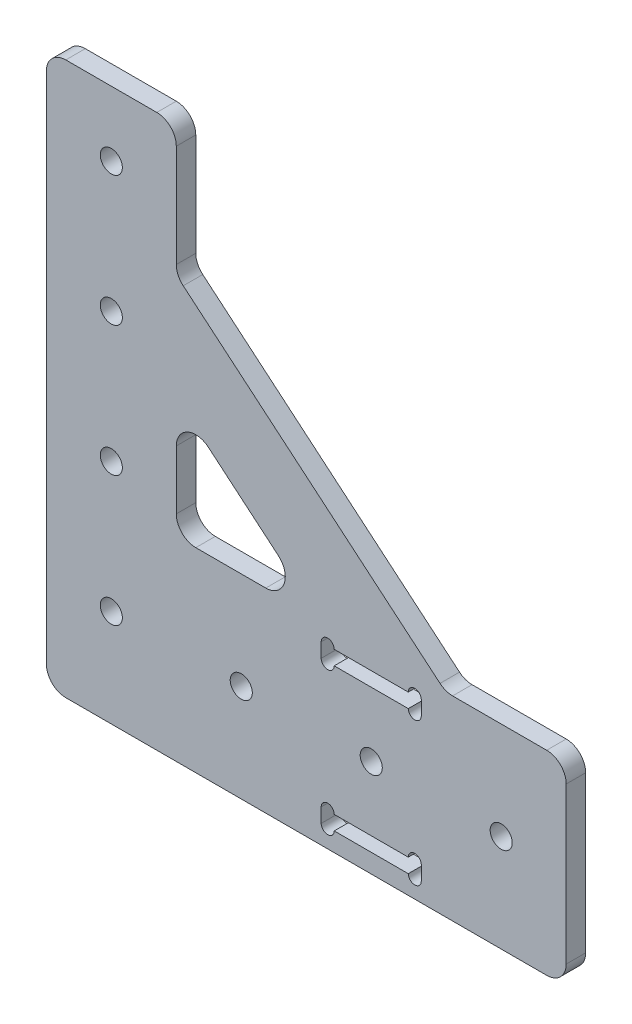
SolidWorks part; units mm, degrees
ref_plane "前视基准面" through (0, 0, 0) normal (0, 0, 1) x (1, 0, 0)
ref_plane "上视基准面" through (0, 0, 0) normal (0, 1, 0) x (1, 0, 0)
ref_plane "右视基准面" through (0, 0, 0) normal (1, 0, 0) x (0, 0, -1)
other "Configuration Table"
sketch "草图1" plane through (0, 0, 0) normal (0, 0, 1) x (1, 0, 0)
  line L0 (0, 85) -> (0, 0)
  line L1 (0, 0) -> (80, 0)
  line L2 (80, 0) -> (80, 30)
  line L3 (80, 30) -> (61.422, 30)
  line L4 (20, 30) -> (20, 48.5)
  line L5 (20, 85) -> (0, 85)
  line L6 (-8.2516, 78.7898) -> (73.8069, 9.7861) construction
  line L7 (20, 48.5) -> (42, 30)
  line L8 (20, 64.8321) -> (20, 85)
  line L9 (20, 64.8321) -> (61.422, 30)
  line L10 (-11.4696, 74.963) -> (70.5889, 5.9593) construction
  line L11 (42, 30) -> (20, 30)
  point P13 (-5.0735, 82.4031)
  point P14 (77.2855, 13.7621)
  dimension "D1" = 20
  dimension "D2" = 30
  dimension "D3" = 85
  dimension "D4" = 80
  dimension "D6" = 18.5
  dimension "D7" = 22
  dimension "D8" = 7.5
  dimension "D5" = 5
extrude "凸台-拉伸1" add sketch "草图1" along normal blind 3
sketch "草图2" plane through (0, 0, 3) normal (0, 0, 1) x (1, 0, 0)
  line L0 (10, 74.6406) -> (10, -4.6406) construction
  line L1 (0, 85) -> (0, 0) construction
  line L2 (80, 0) -> (80, 30) construction
  line L4 (-9.7715, 15) -> (79.7662, 15) construction
  circle A0 centre (10, 75) radius 1.7
  circle A1 centre (10, 55) radius 1.7
  circle A2 centre (10, 35) radius 1.7
  circle A3 centre (30, 15) radius 1.7
  circle A4 centre (50, 15) radius 1.7
  circle A5 centre (70, 15) radius 1.7
  circle A6 centre (10, 15) radius 1.7
  point P12 (80, 15)
  dimension "D2" = 3.4
  dimension "D3" = 20
  dimension "D4" = 20
  dimension "D5" = 20
  dimension "D7" = 3.4
  dimension "D8" = 20
  dimension "D9" = 20
  dimension "D10" = 20
  dimension "D1" = 10
extrude "切除-拉伸1" cut sketch "草图2" against normal through all
sketch "草图3" plane through (0, 0, 3) normal (0, 0, 1) x (1, 0, 0)
  line L0 (57.6, 25) -> (57.6, 27) construction
  line L1 (57.6, 25) -> (42.4, 25) construction
  line L2 (42.4, 25) -> (42.4, 27) construction
  line L3 (57.6, 27) -> (42.4, 27) construction
  line L4 (57.6, 25) -> (57.6, 27) construction
  line L5 (57.6, 25) -> (42.4, 25) construction
  line L6 (42.4, 25) -> (42.4, 27) construction
  line L7 (57.6, 27) -> (42.4, 27) construction
  line L8 (57.7, 24.9) -> (57.7, 27.1)
  line L9 (57.7, 27.1) -> (42.3, 27.1)
  line L10 (42.3, 24.9) -> (42.3, 27.1)
  line L11 (57.7, 24.9) -> (42.3, 24.9)
  line L12 (57.7, 40.7981) -> (57.7, -2.9729) construction
  line L13 (84.1705, 27.1) -> (29.5694, 27.1) construction
  line L14 (80, 0) -> (80, 30) construction
  line L16 (30, 15) -> (70, 15) construction
  line L17 (23.5851, 25) -> (89.6349, 25) construction
  line L18 (23.5851, 5) -> (89.6349, 5) construction
  line L19 (84.1705, 2.9) -> (29.5694, 2.9) construction
  line L20 (57.7, -10.7981) -> (57.7, 32.9729) construction
  line L21 (57.6, 3) -> (42.4, 3) construction
  line L22 (42.4, 5) -> (42.4, 3) construction
  line L23 (57.6, 5) -> (42.4, 5) construction
  line L24 (57.6, 5) -> (57.6, 3) construction
  line L25 (57.7, 5.1) -> (42.3, 5.1)
  line L26 (42.3, 5.1) -> (42.3, 2.9)
  line L27 (57.7, 2.9) -> (42.3, 2.9)
  line L28 (57.7, 5.1) -> (57.7, 2.9)
  dimension "D2" = 15.4
  dimension "D3" = 2.2
  dimension "D4" = 22.3
  dimension "D5" = 2.1
  dimension "D6" = 10
  dimension "D1" = 0.1
extrude "切除-拉伸2" cut sketch "草图3" against normal blind 10
sketch "草图4" plane through (0, 0, 3) normal (0, 0, 1) x (1, 0, 0)
  line L0 (44.3, 27.1) -> (55.7, 27.1)
  line L1 (57.7, 27.1) -> (57.7, 24.9)
  line L2 (55.7, 24.9) -> (44.3, 24.9)
  line L3 (42.3, 24.9) -> (42.3, 27.1)
  line L4 (42.3, 24.9) -> (57.7, 24.9) construction
  line L5 (30, 15) -> (70, 15) construction
  line L6 (42.3, 5.1) -> (42.3, 2.9)
  line L7 (55.7, 5.1) -> (44.3, 5.1)
  line L8 (57.7, 2.9) -> (57.7, 5.1)
  line L9 (44.3, 2.9) -> (55.7, 2.9)
  arc A4 (42.3, 27.1) -> (44.3, 27.1) centre (43.3, 27.1) cw
  arc A5 (42.3, 24.9) -> (44.3, 24.9) centre (43.3, 24.9) ccw
  arc A6 (57.7, 27.1) -> (55.7, 27.1) centre (56.7, 27.1) ccw
  arc A7 (57.7, 24.9) -> (55.7, 24.9) centre (56.7, 24.9) cw
  arc A8 (57.7, 5.1) -> (55.7, 5.1) centre (56.7, 5.1) ccw
  arc A9 (57.7, 2.9) -> (55.7, 2.9) centre (56.7, 2.9) cw
  arc A10 (42.3, 5.1) -> (44.3, 5.1) centre (43.3, 5.1) cw
  arc A11 (42.3, 2.9) -> (44.3, 2.9) centre (43.3, 2.9) ccw
  dimension "D1" = 1
extrude "切除-拉伸3" cut sketch "草图4" against normal blind 10
fillet "圆角1" radius 3 7 edges at (20, 64.8321, 1.5) (61.422, 30, 1.5) (80, 30, 1.5) (80, 0, 1.5) (0, 0, 1.5) (0, 85, 1.5) (20, 85, 1.5)
fillet "圆角2" radius 3 3 edges at (20, 30, 1.5) (20, 48.5, 1.5) (42, 30, 1.5)
